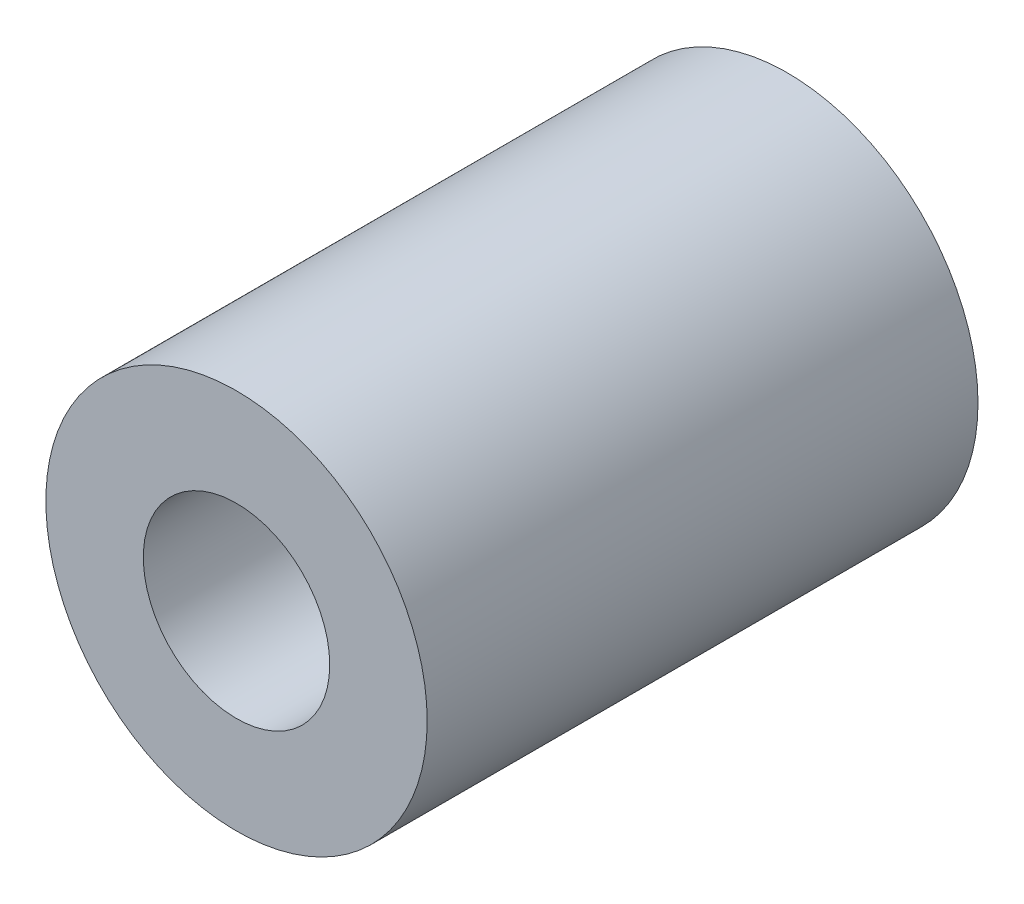
SolidWorks part; units mm, degrees
ref_plane "Front Plane" through (0, 0, 0) normal (0, 0, 1) x (1, 0, 0)
ref_plane "Top Plane" through (0, 0, 0) normal (0, 1, 0) x (1, 0, 0)
ref_plane "Right Plane" through (0, 0, 0) normal (1, 0, 0) x (0, 0, -1)
sketch "S01 - Annular section" plane through (0, 0, 0) normal (0, 0, 1) x (1, 0, 0)
  circle A0 centre (0, 0) radius 4.5
  circle A1 centre (0, 0) radius 2.2
  dimension "D1" = 4.4
  dimension "D2" = 9
extrude "01 - Annular section" add sketch "S01 - Annular section" along normal blind 13
